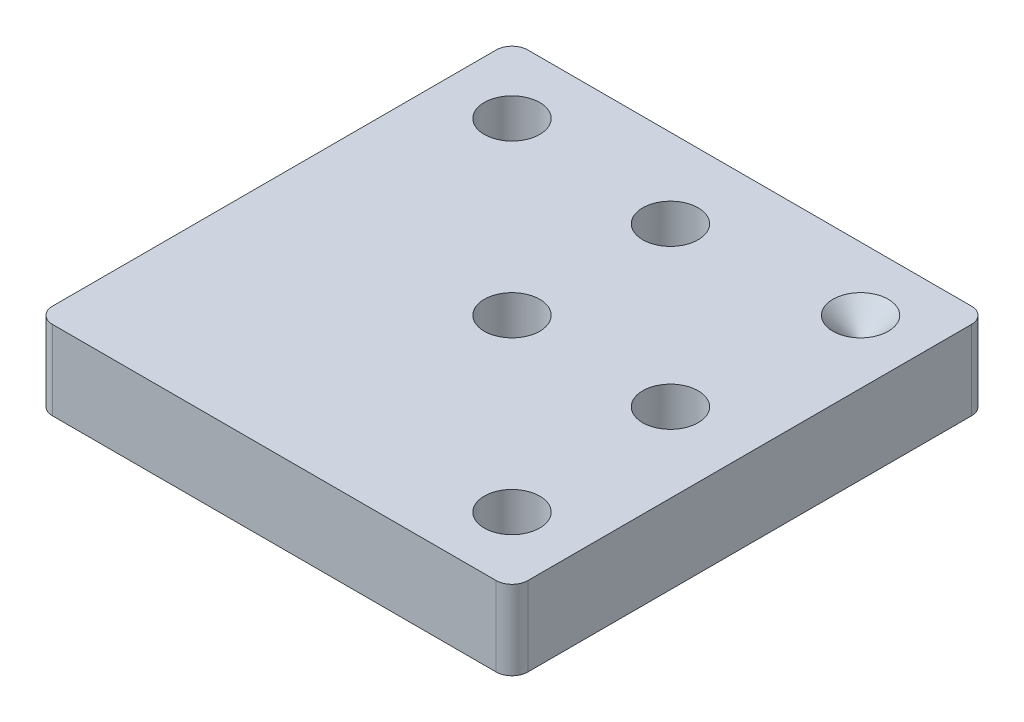
SolidWorks part; units mm, degrees
ref_plane "Front Plane" through (0, 0, 0) normal (0, 0, 1) x (1, 0, 0)
ref_plane "Top Plane" through (0, 0, 0) normal (0, 1, 0) x (1, 0, 0)
ref_plane "Right Plane" through (0, 0, 0) normal (1, 0, 0) x (0, 0, -1)
sketch "Sketch1" plane through (0, 0, 0) normal (0, 1, 0) x (1, 0, 0)
  line L1 (-38.1, 38.1) -> (38.1, 38.1)
  line L2 (-38.1, 38.1) -> (-38.1, -38.1)
  line L3 (-38.1, -38.1) -> (38.1, -38.1)
  line L4 (38.1, 38.1) -> (38.1, -38.1)
  line L5 (-38.1, 38.1) -> (38.1, -38.1) construction
  line L6 (-38.1, -38.1) -> (38.1, 38.1) construction
  point P0 (0, 0)
  dimension "D1" = 76.2
extrude "Boss-Extrude1" add sketch "Sketch1" along normal blind 12.7
sketch "Sketch2" plane through (0, 0, 0) normal (0, -1, 0) x (1, 0, 0)
  circle A1 centre (0, 0) radius 4.445
  point P0 (0, 0)
  dimension "D1" = 8.89
extrude "Cut-Extrude1" cut sketch "Sketch2" against normal up to next
sketch "Sketch6" plane through (0, 12.7, 0) normal (0, 1, 0) x (1, 0, 0)
  line L0 (38.1, 38.1) -> (-38.1, 38.1) construction
  line L1 (-38.1, 38.1) -> (-38.1, -38.1) construction
  line L2 (38.1, -38.1) -> (38.1, 38.1) construction
  line L3 (-38.1, -38.1) -> (38.1, -38.1) construction
  circle A0 centre (-27.3237, 27.3237) radius 4.445
  circle A1 centre (27.3237, -27.3237) radius 4.445
  dimension "D2" = 8.89
  dimension "D6" = 15.24
  dimension "D7" = 15.24
  dimension "D1" = 10.7763
  dimension "D3" = 10.7763
  dimension "D4" = 10.7763
  dimension "D5" = 10.7763
extrude "Cut-Extrude2" cut sketch "Sketch6" against normal up to next
sketch "Sketch7" plane through (0, 12.7, 0) normal (0, 1, 0) x (1, 0, 0)
  line L0 (38.1, 38.1) -> (-38.1, 38.1) construction
  line L1 (38.1, -38.1) -> (38.1, 38.1) construction
  circle A0 centre (27.94, 27.94) radius 4.445
  dimension "D3" = 8.89
  dimension "D1" = 10.16
  dimension "D2" = 10.16
extrude "Cut-Extrude3" cut sketch "Sketch7" against normal blind 3.81 draft 45
sketch "Sketch12" plane through (0, 12.7, 0) normal (0, 1, 0) x (1, 0, 0)
  line L0 (38.1, 38.1) -> (-38.1, 38.1) construction
  line L1 (38.1, -38.1) -> (38.1, 38.1) construction
  circle A0 centre (0, 25.4) radius 4.445
  circle A1 centre (25.4, 0) radius 4.445
  dimension "D2" = 38.1
  dimension "D3" = 8.89
  dimension "D4" = 12.7
  dimension "D5" = 38.1
  dimension "D1" = 12.7
extrude "Cut-Extrude4" cut sketch "Sketch12" against normal up to next
sketch "Sketch13" plane through (0, 0, 0) normal (0, -1, 0) x (1, 0, 0)
  circle A0 centre (25.4, 0) radius 4.445 construction
  circle A1 centre (0, -25.4) radius 4.445 construction
  circle A6 centre (0, -25.4) radius 6.858
  circle A9 centre (25.4, 0) radius 6.858
  point P2 (0, 0)
  dimension "D1" = 13.716
  dimension "D2" = 13.716
extrude "Cut-Extrude5" cut sketch "Sketch13" against normal blind 3.81
fillet "Fillet1" radius 2.54 4 edges at (-38.1, 6.35, 38.1) (38.1, 6.35, 38.1) (38.1, 6.35, -38.1) (-38.1, 6.35, -38.1)
